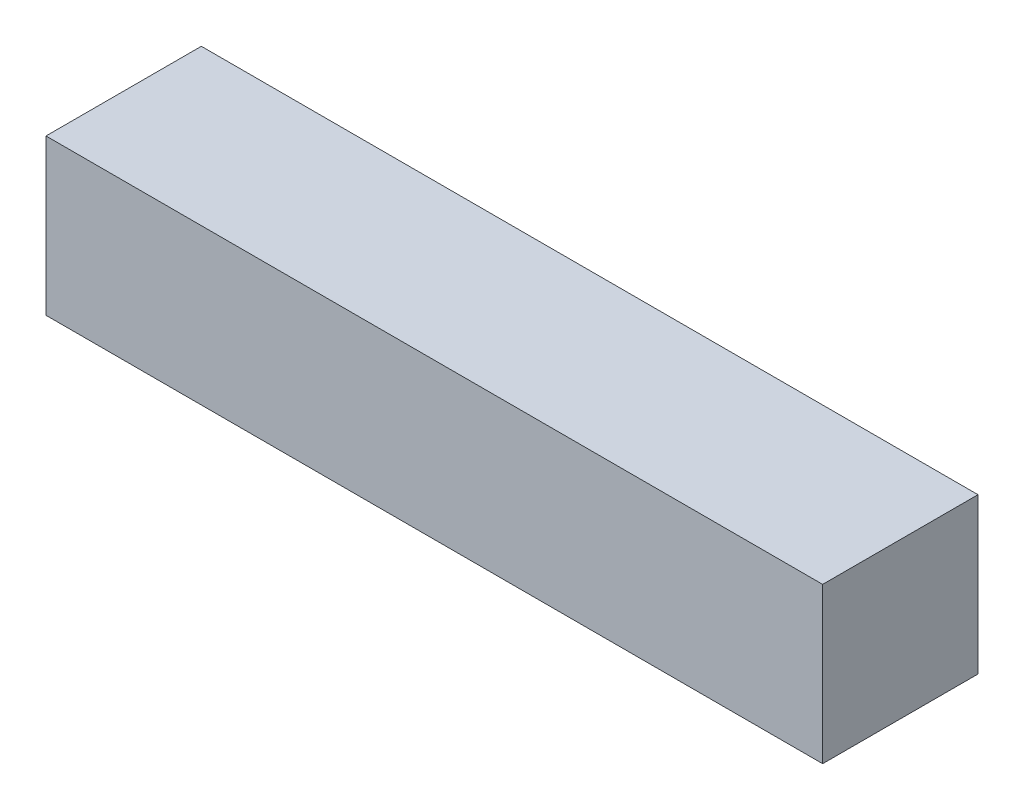
SolidWorks part; units mm, degrees
material "ABS PC"
ref_plane "Front Plane" through (0, 0, 0) normal (0, 0, 1) x (1, 0, 0)
ref_plane "Top Plane" through (0, 0, 0) normal (0, 1, 0) x (1, 0, 0)
ref_plane "Right Plane" through (0, 0, 0) normal (1, 0, 0) x (0, 0, -1)
sketch "Sketch1" plane through (0, 0, 0) normal (1, 0, 0) x (0, 0, -1)
  line L1 (0, 0) -> (12.7, 0)
  line L2 (0, 0) -> (0, 12.7)
  line L3 (0, 12.7) -> (12.7, 12.7)
  line L4 (12.7, 0) -> (12.7, 12.7)
  dimension "D1" = 12.7
  dimension "D2" = 12.7
extrude "Boss-Extrude1" add sketch "Sketch1" along normal blind 63.5
